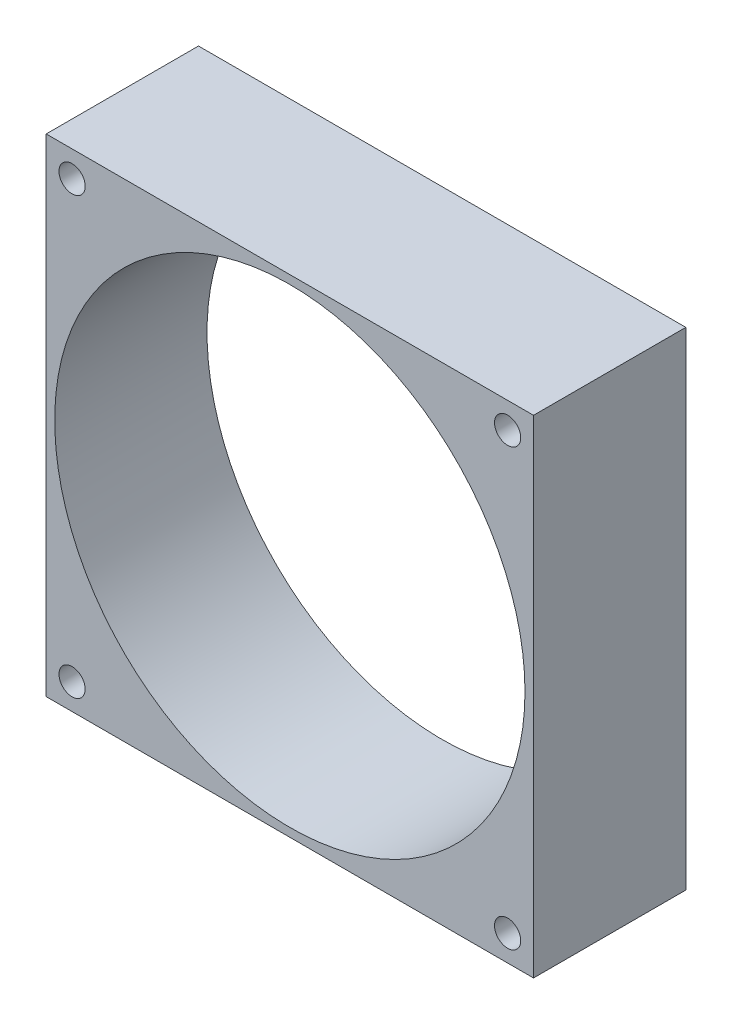
SolidWorks part; units mm, degrees
ref_plane "Front Plane" through (0, 0, 0) normal (0, 0, 1) x (1, 0, 0)
ref_plane "Top Plane" through (0, 0, 0) normal (0, 1, 0) x (1, 0, 0)
ref_plane "Right Plane" through (0, 0, 0) normal (1, 0, 0) x (0, 0, -1)
sketch "Sketch1" plane through (0, 0, 0) normal (0, 0, 1) x (1, 0, 0)
  line L0 (40, 80) -> (40, 0) construction
  line L1 (0, 0) -> (80, 0)
  line L2 (0, 0) -> (0, 80)
  line L3 (0, 80) -> (80, 80)
  line L4 (80, 0) -> (80, 80)
  line L5 (4.25, 80) -> (4.25, 0) construction
  line L6 (0, 75.75) -> (80, 75.75) construction
  line L7 (0, 40) -> (80, 40) construction
  circle A0 centre (40, 40) radius 38.6
  circle A1 centre (40, 40) radius 45.8 construction
  circle A2 centre (4.25, 75.75) radius 2.15
  circle A3 centre (75.75, 75.75) radius 2.15
  circle A4 centre (4.25, 4.25) radius 2.15
  circle A5 centre (75.75, 4.25) radius 2.15
  point P20 (0, 0)
  dimension "D3" = 77.2
  dimension "D4" = 91.6
  dimension "D7" = 4.3
  dimension "D1" = 80
  dimension "D2" = 80
  dimension "D5" = 35.75
  dimension "D6" = 35.75
extrude "Boss-Extrude1" add sketch "Sketch1" along normal blind 25
